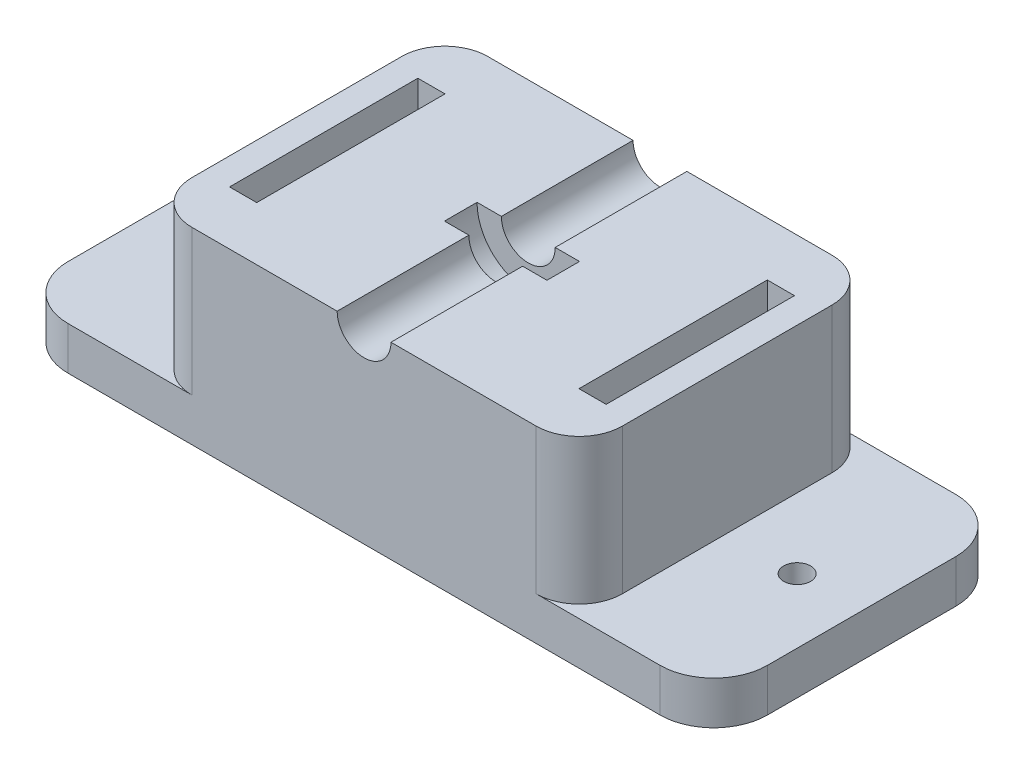
SolidWorks part; units mm, degrees
ref_plane "Alzado" through (0, 0, 0) normal (0, 0, 1) x (1, 0, 0)
ref_plane "Planta" through (0, 0, 0) normal (0, 1, 0) x (1, 0, 0)
ref_plane "Vista lateral" through (0, 0, 0) normal (1, 0, 0) x (0, 0, -1)
sketch "Croquis1" plane through (0, 0, 0) normal (0, 0, 1) x (1, 0, 0)
  line L0 (-40, 0) -> (40, 0)
  line L1 (40, 0) -> (40, -27)
  line L2 (40, -35) -> (-40, -35)
  line L3 (-40, -27) -> (-40, 0)
  line L5 (-40, -35) -> (-65, -35)
  line L7 (-40, -27) -> (-65, -27)
  line L8 (-65, -35) -> (-65, -27)
  line L9 (40, -35) -> (65, -35)
  line L11 (40, -27) -> (65, -27)
  line L12 (65, -35) -> (65, -27)
  dimension "D1" = 80
  dimension "D4" = 25
  dimension "D2" = 35
  dimension "D3" = 25
  dimension "D5" = 8
  dimension "D6" = 8
extrude "Saliente-Extruir1" add sketch "Croquis1" along normal blind 55
ref_plane "Plano1" through (0, 0, 27.5) normal (0, 0, 1) x (1, 0, 0)
sketch "Croquis2" plane through (0, 0, 27.5) normal (0, 0, 1) x (1, 0, 0)
  circle A0 centre (0, 0) radius 9.525
  dimension "D1" = 19.05
extrude "Cortar-Extruir1" cut sketch "Croquis2" against normal mid plane 6.05
sketch "Croquis3" plane through (0, 0, 0) normal (0, 1, 0) x (1, 0, 0)
  line L0 (40, 0) -> (-40, 0) construction
  line L1 (-35, -10) -> (-29.95, -10)
  line L2 (-35, -10) -> (-35, -45)
  line L3 (-35, -45) -> (-29.95, -45)
  line L4 (-29.95, -10) -> (-29.95, -45)
  line L10 (-40, -55) -> (-40, 0) construction
  line L11 (0, 20.6246) -> (0, -67.1314) construction
  line L12 (35, -45) -> (29.95, -45)
  line L13 (29.95, -10) -> (29.95, -45)
  line L14 (35, -10) -> (29.95, -10)
  line L15 (35, -10) -> (35, -45)
  point P10 (-29.95, -27.5)
  dimension "D1" = 35
  dimension "D2" = 27.5
  dimension "D3" = 5.05
  dimension "D7" = 5
extrude "Cortar-Extruir2" cut sketch "Croquis3" against normal blind 10
sketch "Croquis4" plane through (0, 0, 27.5) normal (0, 0, 1) x (1, 0, 0)
  circle A0 centre (0, 0) radius 5
  dimension "D1" = 10
extrude "Cortar-Extruir3" cut sketch "Croquis4" against normal through all both and the other way through all
fillet "Redondeo1" radius 10 4 edges at (65, -31, 0) (65, -31, 55) (-65, -31, 0) (-65, -31, 55)
sketch "Croquis5" plane through (0, -27, 0) normal (0, 1, 0) x (1, 0, 0)
  line L0 (0, 11.3752) -> (0, -14.9619) construction
  line L2 (-40, -55) -> (-55, -55) construction
  circle A0 centre (-53, -27.5) radius 2.5
  circle A2 centre (53, -27.5) radius 2.5
  dimension "D1" = 5
  dimension "D2" = 53
  dimension "D3" = 27.5
extrude "Cortar-Extruir4" cut sketch "Croquis5" against normal through all
fillet "Redondeo2" radius 8 4 edges at (-40, -13.5, 0) (40, -13.5, 0) (40, -13.5, 55) (-40, -13.5, 55)
